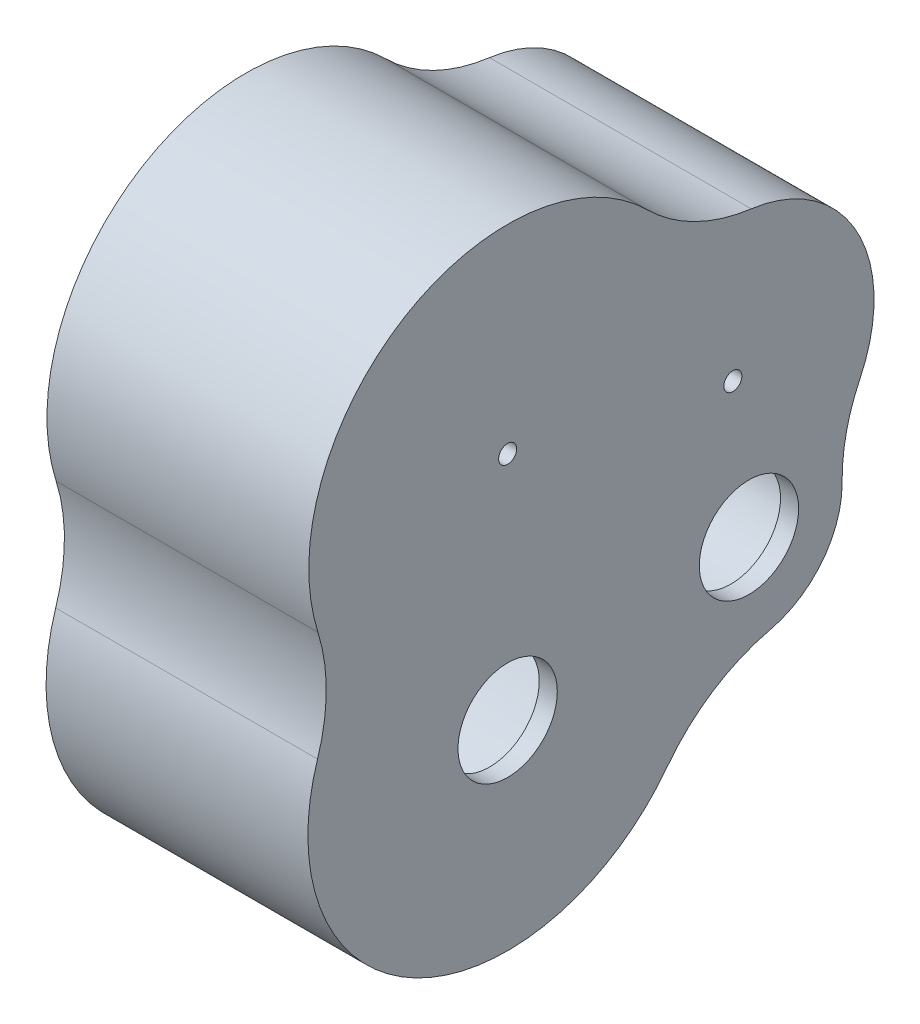
SolidWorks part; units mm, degrees
ref_plane "Спереди" through (0, 0, 0) normal (0, 0, 1) x (1, 0, 0)
ref_plane "Сверху" through (0, 0, 0) normal (0, 1, 0) x (1, 0, 0)
ref_plane "Справа" through (0, 0, 0) normal (1, 0, 0) x (0, 0, -1)
sketch "Эскиз1" plane through (0, 0, 0) normal (1, 0, 0) x (0, 0, -1)
  circle A0 centre (0, 0) radius 5.5
  circle A1 centre (0, 25.54) radius 1
  circle A2 centre (24.9423, 20.047) radius 1
  circle A3 centre (26.7245, 4.1838) radius 5.5
  circle A4 centre (0, 0) radius 18.125 construction
  circle A5 centre (0, 25.54) radius 18.025 construction
  circle A6 centre (0, 25.54) radius 9.825 construction
  circle A7 centre (24.9423, 20.047) radius 11.64 construction
  circle A8 centre (26.7245, 4.1838) radius 6.32 construction
  arc A13 (18.8645, 32.258) -> (-15.4896, 12.8486) centre (0, 25.54) ccw
  arc A18 (20.1067, -0.8587) -> (33.3067, 9.2727) centre (26.7245, 4.1838) ccw
  circle A20 centre (0, 25.54) radius 20.025 construction
  circle A22 centre (26.7245, 4.1838) radius 8.32 construction
  arc A23 (33.3067, 9.2727) -> (18.8645, 32.258) centre (24.9423, 20.047) ccw
  arc A24 (-15.4896, 12.8486) -> (20.1067, -0.8587) centre (0, 0) ccw
  dimension "D1" = 11
  dimension "D7" = 2
  dimension "D8" = 2
  dimension "D9" = 11
  dimension "D10" = 36.25
  dimension "D11" = 36.05
  dimension "D12" = 19.65
  dimension "D13" = 23.28
  dimension "D14" = 12.64
  dimension "D2" = 25.54
  dimension "D3" = 25.54
  dimension "D4" = 32
  dimension "D5" = 27.05
  dimension "D6" = 15.963
  dimension "D15" = 2
extrude "Вытянуть-Тонкостенный1" add sketch "Эскиз1" along normal mid plane 25 thin
sketch "Эскиз2" plane through (12.5, 0, 0) normal (1, 0, 0) x (0, 0, -1)
  circle A21 centre (26.7245, 4.1838) radius 5.5
  circle A22 centre (26.7245, 4.1838) radius 5.5
  circle A23 centre (24.9423, 20.047) radius 1
  circle A24 centre (24.9423, 20.047) radius 1
  circle A25 centre (0, 25.54) radius 1
  circle A26 centre (0, 25.54) radius 1
  circle A27 centre (0, 0) radius 5.5
  circle A28 centre (0, 0) radius 5.5
  arc A32 (18.8645, 32.258) -> (-15.4896, 12.8486) centre (0, 25.54) ccw
  arc A33 (33.3067, 9.2727) -> (18.8645, 32.258) centre (24.9423, 20.047) ccw
  arc A34 (20.1067, -0.8587) -> (33.3067, 9.2727) centre (26.7245, 4.1838) ccw
  arc A35 (-15.4896, 12.8486) -> (20.1067, -0.8587) centre (0, 0) ccw
  arc A36 (18.8645, 32.258) -> (-15.4896, 12.8486) centre (0, 25.54) ccw
  arc A37 (33.3067, 9.2727) -> (18.8645, 32.258) centre (24.9423, 20.047) ccw
  arc A38 (20.1067, -0.8587) -> (33.3067, 9.2727) centre (26.7245, 4.1838) ccw
  arc A39 (-15.4896, 12.8486) -> (20.1067, -0.8587) centre (0, 0) ccw
  arc M17 (19.9515, 34.8693) -> (-18.0063, 12.8564) centre (0, 25.54) ccw
  arc M18 (-18.0063, 12.8564) -> (21.6034, -4.7759) centre (0, 0) ccw
  arc M19 (21.6034, -4.7759) -> (35.9069, 8.894) centre (26.7245, 4.1838) ccw
  arc M20 (35.9069, 8.894) -> (19.9515, 34.8693) centre (24.9423, 20.047) ccw
  arc M21 (20.1067, -0.8587) -> (-15.4896, 12.8486) centre (0, 0) cw
  arc M22 (-15.4896, 12.8486) -> (18.8645, 32.258) centre (0, 25.54) cw
  arc M23 (18.8645, 32.258) -> (33.3067, 9.2727) centre (24.9423, 20.047) cw
  arc M24 (33.3067, 9.2727) -> (20.1067, -0.8587) centre (26.7245, 4.1838) cw
  dimension "D1" = 0
  dimension "D2" = 0
  dimension "D3" = 0
  dimension "D4" = 0
  dimension "D5" = 0
extrude "Бобышка-Вытянуть1" add sketch "Эскиз2" along normal blind 2 contours M20 M17 M18 M19 M24 M21 M22 M23 | A28 A26 A24 A22 M21 M24 M23 M22
mirror "Зеркальное отражение1" about plane through (0, 0, 0) normal (1, 0, 0) of "Бобышка-Вытянуть1"
fillet "Скругление1" radius 20 4 edges at (0, 34.8693, -19.9515) (0, 8.894, -35.9069) (0, -4.7759, -21.6034) (0, 12.8564, 18.0063)
fillet "Скругление2" radius 1 12 edges at (0, 9.2727, -33.3067) (0, 32.258, -18.8645) (0, 12.8486, 15.4896) (0, -0.8587, -20.1067) (12.5, -2.4163, -31.7902) (-12.5, -2.4163, -31.7902) (12.5, 42.9748, 9.8503) (-12.5, 42.9748, 9.8503) (12.5, 27.3037, -36.4917) (-12.5, 27.3037, -36.4917) (12.5, -18.7807, 7.232) (-12.5, -18.7807, 7.232)
equation "\"D1@Вытянуть-Тонкостенный1\"=(12*2)+1"
